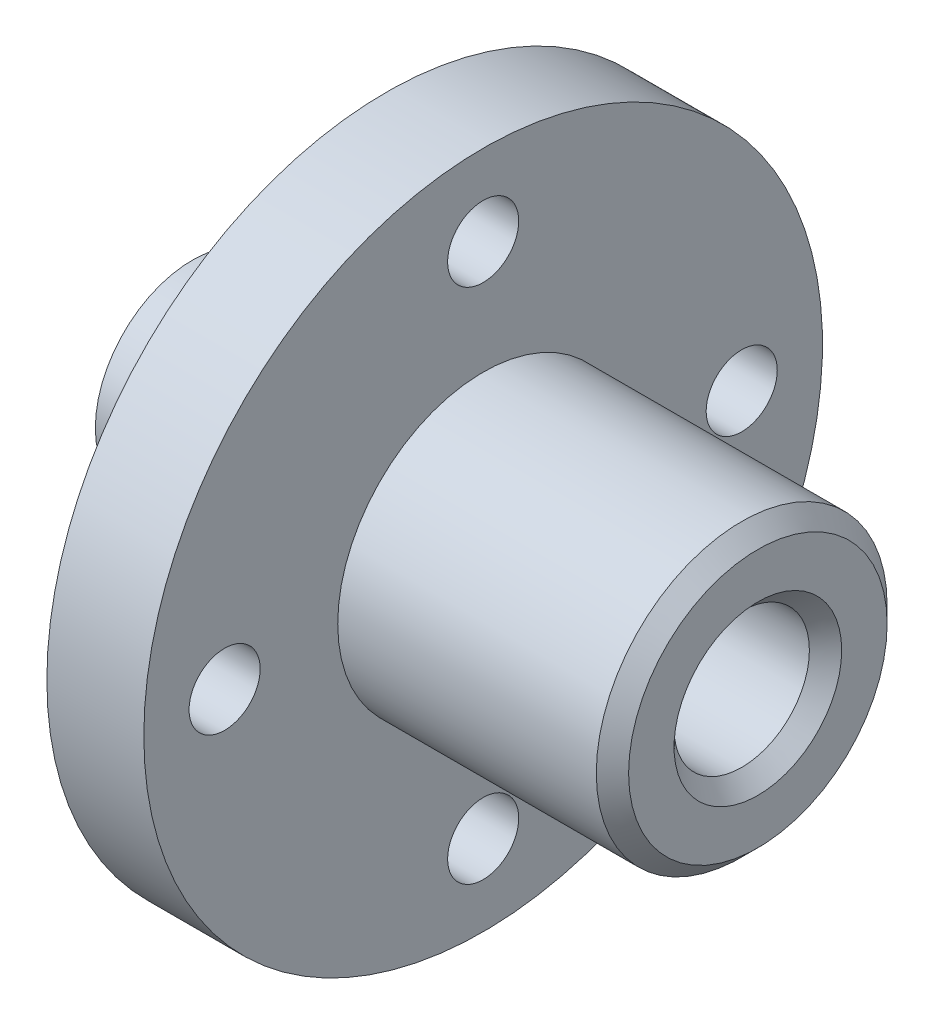
SolidWorks part; units mm, degrees
ref_plane "Спереди" through (0, 0, 0) normal (0, 0, 1) x (1, 0, 0)
ref_plane "Сверху" through (0, 0, 0) normal (0, 1, 0) x (1, 0, 0)
ref_plane "Справа" through (0, 0, 0) normal (1, 0, 0) x (0, 0, -1)
sketch "Эскиз1" plane through (0, 0, 0) normal (0, 0, 1) x (1, 0, 0)
  line L0 (0, 0) -> (64.7049, 0) construction
  line L1 (0, -3.5) -> (0, -6)
  line L2 (0, -6) -> (6.2, -6)
  line L3 (0, -3.5) -> (17, -3.5)
  line L4 (17, -3.5) -> (19.0207, 0)
  line L5 (6.2, -6) -> (6.2, -11)
  line L6 (6.2, -11) -> (8.2, -11)
  line L7 (8.2, -11) -> (8.2, -10.75)
  line L8 (8.2, -10.75) -> (12, -10.75)
  line L9 (12, -10.75) -> (12, -21)
  line L10 (12, -21) -> (18, -21)
  line L11 (18, -21) -> (18, -9)
  line L12 (18, -9) -> (35, -9)
  line L13 (35, -9) -> (35, -4.188)
  line L14 (35, -4.188) -> (25, -4.188)
  line L15 (25, -4.188) -> (22.5821, 0)
  line L16 (22.5821, 0) -> (19.0207, 0)
  dimension "D1" = 7
  dimension "D2" = 12
  dimension "D3" = 6.2
  dimension "D4" = 17
  dimension "D5" = 60
  dimension "D6" = 60
  dimension "D7" = 8.376
  dimension "D8" = 10
  dimension "D9" = 35
  dimension "D10" = 17
  dimension "D11" = 12
  dimension "D12" = 42
  dimension "D13" = 22
  dimension "D14" = 21.5
  dimension "D15" = 2
  dimension "D16" = 18
revolve "Повернуть1" add sketch "Эскиз1" angle 360 about L0
cosmetic thread "Условное изображение резьбы1" parameters "D2"=10
chamfer "Фаска1" distance 1 angle 45 2 edges at (35, 0, 9) (35, 0, 4.188)
sketch "Эскиз2" plane through (12, 0, 0) normal (-1, 0, 0) x (0, 0, 1)
  circle A0 centre (0, 16) radius 2.2
  dimension "D2" = 4.4
  dimension "D1" = 16
extrude "Вырез-Вытянуть1" cut sketch "Эскиз2" against normal through all
pattern_circular "Круговой массив1" count 4 over 360 about axis through (0, 0, 0) along (1, 0, 0) of "Вырез-Вытянуть1"
